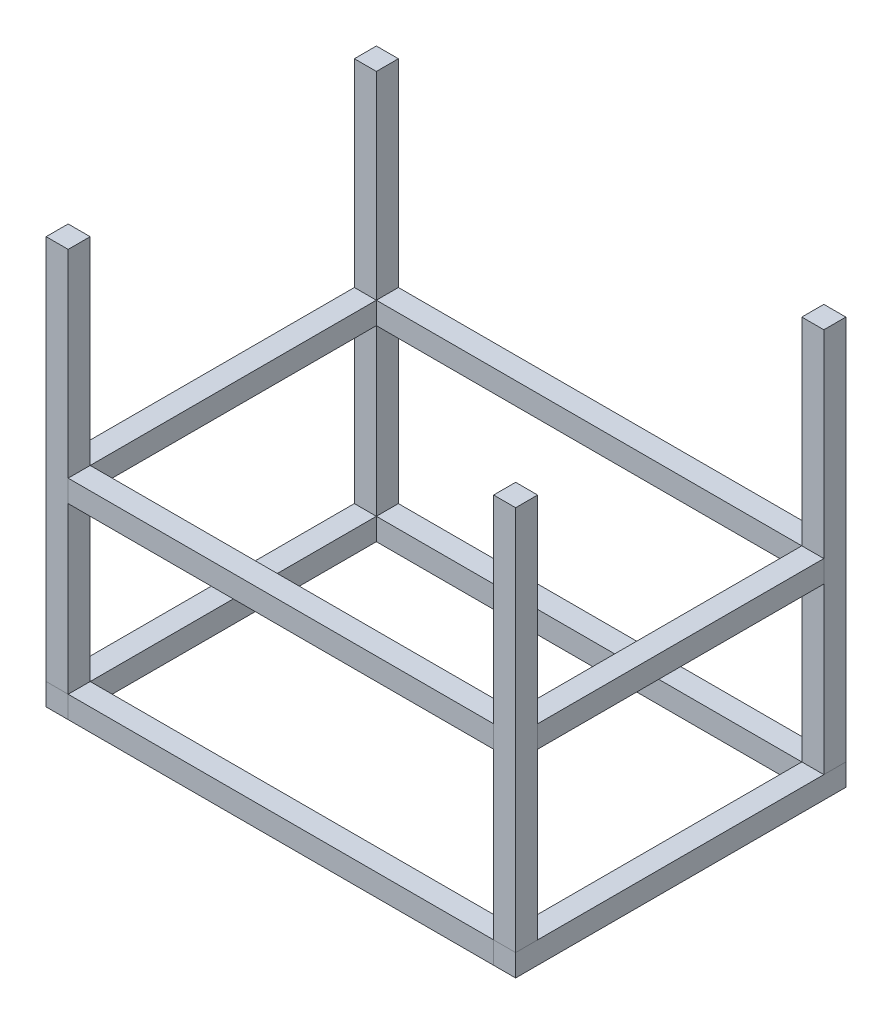
SolidWorks part; units mm, degrees
ref_plane "Front Plane" through (0, 0, 0) normal (0, 0, 1) x (1, 0, 0)
ref_plane "Top Plane" through (0, 0, 0) normal (0, 1, 0) x (1, 0, 0)
ref_plane "Right Plane" through (0, 0, 0) normal (1, 0, 0) x (0, 0, -1)
sketch "ｽｹｯﾁ5" plane through (0, 0, 0) normal (0, 0, 1) x (1, 0, 0)
  line L1 (18.2357, 0) -> (58.2357, 0)
  line L2 (18.2357, 0) -> (18.2357, -40)
  line L3 (18.2357, -40) -> (58.2357, -40)
  line L4 (58.2357, 0) -> (58.2357, -40)
  line L5 (831.2357, 0) -> (871.2357, 0)
  line L6 (831.2357, 0) -> (831.2357, -40)
  line L7 (831.2357, -40) -> (871.2357, -40)
  line L8 (871.2357, 0) -> (871.2357, -40)
  dimension "D1" = 40
  dimension "D2" = 40
  dimension "D3" = 40
  dimension "D4" = 40
  dimension "D5" = 773
extrude "ﾎﾞｽ - 押し出し3" add sketch "ｽｹｯﾁ5" along normal blind 600
sketch "ｽｹｯﾁ6" plane through (58.2357, 0, 0) normal (1, 0, 0) x (0, 0, -1)
  line L0 (-600, -40) -> (0, -40) construction
  line L1 (-600, 0) -> (-560, 0)
  line L2 (-600, 0) -> (-600, -40)
  line L3 (-600, -40) -> (-560, -40)
  line L4 (-560, 0) -> (-560, -40)
  line L6 (0, 0) -> (-39.9984, 0)
  line L7 (0, 0) -> (0, -40)
  line L8 (0, -40) -> (-39.9984, -40)
  line L9 (-39.9984, 0) -> (-39.9984, -40)
  dimension "D1" = 40
  dimension "D2" = 40
  dimension "D3" = 40
  dimension "D4" = 39.9984
extrude "ﾎﾞｽ - 押し出し5" add sketch "ｽｹｯﾁ6" along normal blind 773 separate body
sketch "ｽｹｯﾁ7" plane through (0, 0, 0) normal (0, 1, 0) x (1, 0, 0)
  line L0 (871.2357, -600) -> (871.2357, 0) construction
  line L17 (18.2357, 0) -> (58.2357, 0)
  line L18 (18.2357, 0) -> (18.2357, -39.9984)
  line L19 (18.2357, -39.9984) -> (58.2357, -39.9984)
  line L20 (58.2357, 0) -> (58.2357, -39.9984)
  line L21 (831.2357, 0) -> (871.2357, 0)
  line L22 (831.2357, 0) -> (831.2357, -39.9984)
  line L23 (831.2357, -39.9984) -> (871.2357, -39.9984)
  line L24 (871.2357, 0) -> (871.2357, -39.9984)
  line L25 (58.2357, -600) -> (18.2357, -600) construction
  line L26 (58.2357, -560) -> (18.2357, -560)
  line L27 (58.2357, -560) -> (58.2357, -600)
  line L28 (58.2357, -600) -> (18.2357, -600)
  line L29 (18.2357, -560) -> (18.2357, -600)
  line L30 (18.2357, -600) -> (18.2357, 0) construction
  line L32 (831.2357, -560) -> (871.2357, -560)
  line L33 (831.2357, -560) -> (831.2357, -600)
  line L34 (831.2357, -600) -> (871.2357, -600)
  line L35 (871.2357, -560) -> (871.2357, -600)
extrude "ﾎﾞｽ - 押し出し6" add sketch "ｽｹｯﾁ7" along normal blind 700 separate body
sketch "ｽｹｯﾁ10" plane through (58.2357, 0, 0) normal (1, 0, 0) x (0, 0, -1)
  line L0 (-600, 700) -> (-600, 0) construction
  line L1 (-600, 340) -> (-560, 340)
  line L2 (-600, 340) -> (-600, 300)
  line L3 (-600, 300) -> (-560, 300)
  line L4 (-560, 340) -> (-560, 300)
  line L5 (-560, 700) -> (-560, 0) construction
  line L6 (-600, 700) -> (-560, 700) construction
  line L7 (-39.9984, 700) -> (-39.9984, 0) construction
  line L8 (-39.9984, 340) -> (0, 340)
  line L9 (-39.9984, 340) -> (-39.9984, 300)
  line L10 (-39.9984, 300) -> (0, 300)
  line L11 (0, 340) -> (0, 300)
  line L12 (0, 700) -> (0, 0) construction
  dimension "D1" = 40
  dimension "D2" = 360
extrude "ﾎﾞｽ - 押し出し9" add sketch "ｽｹｯﾁ10" along normal blind 773 separate body
sketch "ｽｹｯﾁ11" plane through (0, 0, 560) normal (0, 0, -1) x (-1, 0, 0)
  line L0 (-871.2357, 700) -> (-871.2357, 0) construction
  line L1 (-831.2357, 340) -> (-871.2357, 340)
  line L2 (-831.2357, 340) -> (-831.2357, 300)
  line L3 (-831.2357, 300) -> (-871.2357, 300)
  line L4 (-871.2357, 340) -> (-871.2357, 300)
  line L5 (-18.2357, 700) -> (-18.2357, 0) construction
  line L6 (-58.2357, 340) -> (-18.2357, 340)
  line L7 (-58.2357, 340) -> (-58.2357, 300)
  line L8 (-58.2357, 300) -> (-18.2357, 300)
  line L9 (-18.2357, 340) -> (-18.2357, 300)
  dimension "D1" = 40
  dimension "D2" = 40
extrude "ﾎﾞｽ - 押し出し10" add sketch "ｽｹｯﾁ11" along normal blind 520 separate body
